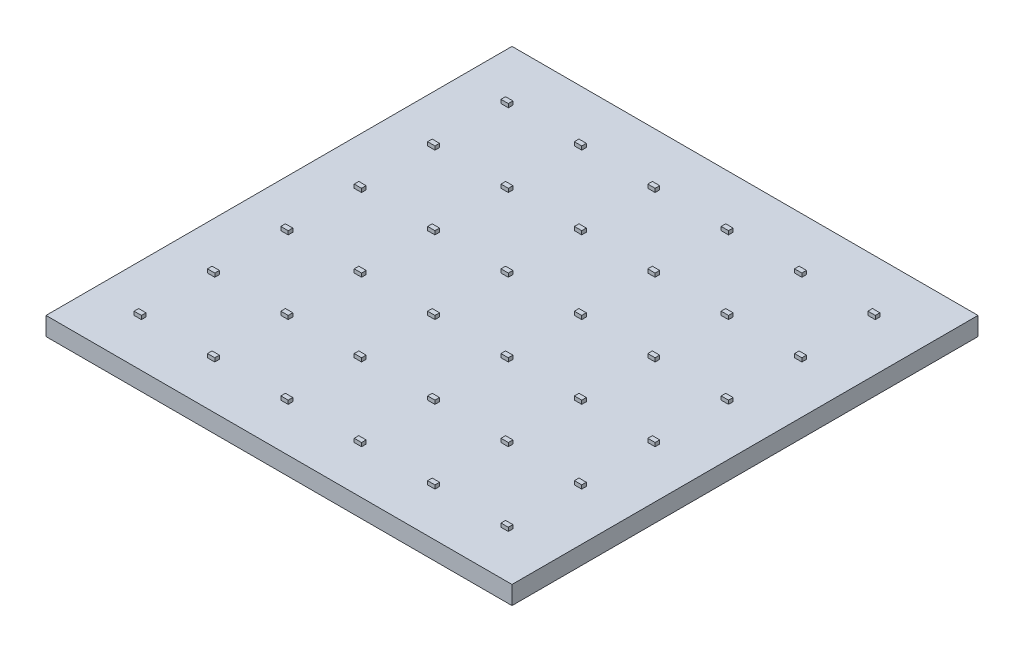
SolidWorks part; units mm, degrees
ref_plane "Front Plane" through (0, 0, 0) normal (0, 0, 1) x (1, 0, 0)
ref_plane "Top Plane" through (0, 0, 0) normal (0, 1, 0) x (1, 0, 0)
ref_plane "Right Plane" through (0, 0, 0) normal (1, 0, 0) x (0, 0, -1)
sketch "Sketch4" plane through (0, 0, 0) normal (0, 1, 0) x (1, 0, 0)
  line L1 (-74.2664, 89.4273) -> (52.7336, 89.4273)
  line L2 (-74.2664, 89.4273) -> (-74.2664, -37.5727)
  line L3 (-74.2664, -37.5727) -> (52.7336, -37.5727)
  line L4 (52.7336, 89.4273) -> (52.7336, -37.5727)
  dimension "D1" = 127
  dimension "D2" = 127
extrude "Boss-Extrude5" add sketch "Sketch4" along normal blind 5
sketch "Sketch5" plane through (0, 5, 0) normal (0, 1, 0) x (1, 0, 0)
  line L0 (-42.2664, -25.5727) -> (-42.2664, -24.3227)
  line L1 (-62.2664, -25.5727) -> (-60.2664, -25.5727)
  line L2 (-62.2664, -25.5727) -> (-62.2664, -24.3227)
  line L3 (-62.2664, -24.3227) -> (-60.2664, -24.3227)
  line L4 (-60.2664, -25.5727) -> (-60.2664, -24.3227)
  line L5 (-42.2664, -25.5727) -> (-40.2664, -25.5727)
  line L6 (-40.2664, -25.5727) -> (-40.2664, -24.3227)
  line L7 (-42.2664, -24.3227) -> (-40.2664, -24.3227)
  line L8 (-22.2664, -25.5727) -> (-22.2664, -24.3227)
  line L9 (-22.2664, -25.5727) -> (-20.2664, -25.5727)
  line L10 (-20.2664, -25.5727) -> (-20.2664, -24.3227)
  line L11 (-22.2664, -24.3227) -> (-20.2664, -24.3227)
  line L12 (-2.2664, -25.5727) -> (-2.2664, -24.3227)
  line L13 (-2.2664, -25.5727) -> (-0.2664, -25.5727)
  line L14 (-0.2664, -25.5727) -> (-0.2664, -24.3227)
  line L15 (-2.2664, -24.3227) -> (-0.2664, -24.3227)
  line L16 (17.7336, -25.5727) -> (17.7336, -24.3227)
  line L17 (17.7336, -25.5727) -> (19.7336, -25.5727)
  line L18 (19.7336, -25.5727) -> (19.7336, -24.3227)
  line L19 (17.7336, -24.3227) -> (19.7336, -24.3227)
  line L20 (37.7336, -25.5727) -> (37.7336, -24.3227)
  line L21 (37.7336, -25.5727) -> (39.7336, -25.5727)
  line L22 (39.7336, -25.5727) -> (39.7336, -24.3227)
  line L23 (37.7336, -24.3227) -> (39.7336, -24.3227)
  line L24 (-42.2664, -5.5727) -> (-42.2664, -4.3227)
  line L25 (-42.2664, -5.5727) -> (-40.2664, -5.5727)
  line L26 (-40.2664, -5.5727) -> (-40.2664, -4.3227)
  line L27 (-42.2664, -4.3227) -> (-40.2664, -4.3227)
  line L28 (-22.2664, -5.5727) -> (-22.2664, -4.3227)
  line L29 (-22.2664, -5.5727) -> (-20.2664, -5.5727)
  line L30 (-20.2664, -5.5727) -> (-20.2664, -4.3227)
  line L31 (-22.2664, -4.3227) -> (-20.2664, -4.3227)
  line L32 (-2.2664, -5.5727) -> (-2.2664, -4.3227)
  line L33 (-2.2664, -5.5727) -> (-0.2664, -5.5727)
  line L34 (-0.2664, -5.5727) -> (-0.2664, -4.3227)
  line L35 (-2.2664, -4.3227) -> (-0.2664, -4.3227)
  line L36 (17.7336, -5.5727) -> (17.7336, -4.3227)
  line L37 (17.7336, -5.5727) -> (19.7336, -5.5727)
  line L38 (19.7336, -5.5727) -> (19.7336, -4.3227)
  line L39 (17.7336, -4.3227) -> (19.7336, -4.3227)
  line L40 (37.7336, -5.5727) -> (37.7336, -4.3227)
  line L41 (37.7336, -5.5727) -> (39.7336, -5.5727)
  line L42 (39.7336, -5.5727) -> (39.7336, -4.3227)
  line L43 (37.7336, -4.3227) -> (39.7336, -4.3227)
  line L44 (-42.2664, 14.4273) -> (-42.2664, 15.6773)
  line L45 (-42.2664, 14.4273) -> (-40.2664, 14.4273)
  line L46 (-40.2664, 14.4273) -> (-40.2664, 15.6773)
  line L47 (-42.2664, 15.6773) -> (-40.2664, 15.6773)
  line L48 (-22.2664, 14.4273) -> (-22.2664, 15.6773)
  line L49 (-22.2664, 14.4273) -> (-20.2664, 14.4273)
  line L50 (-20.2664, 14.4273) -> (-20.2664, 15.6773)
  line L51 (-22.2664, 15.6773) -> (-20.2664, 15.6773)
  line L52 (-2.2664, 14.4273) -> (-2.2664, 15.6773)
  line L53 (-2.2664, 14.4273) -> (-0.2664, 14.4273)
  line L54 (-0.2664, 14.4273) -> (-0.2664, 15.6773)
  line L55 (-2.2664, 15.6773) -> (-0.2664, 15.6773)
  line L56 (17.7336, 14.4273) -> (17.7336, 15.6773)
  line L57 (17.7336, 14.4273) -> (19.7336, 14.4273)
  line L58 (19.7336, 14.4273) -> (19.7336, 15.6773)
  line L59 (17.7336, 15.6773) -> (19.7336, 15.6773)
  line L60 (37.7336, 14.4273) -> (37.7336, 15.6773)
  line L61 (37.7336, 14.4273) -> (39.7336, 14.4273)
  line L62 (39.7336, 14.4273) -> (39.7336, 15.6773)
  line L63 (37.7336, 15.6773) -> (39.7336, 15.6773)
  line L64 (-42.2664, 34.4273) -> (-42.2664, 35.6773)
  line L65 (-42.2664, 34.4273) -> (-40.2664, 34.4273)
  line L66 (-40.2664, 34.4273) -> (-40.2664, 35.6773)
  line L67 (-42.2664, 35.6773) -> (-40.2664, 35.6773)
  line L68 (-22.2664, 34.4273) -> (-22.2664, 35.6773)
  line L69 (-22.2664, 34.4273) -> (-20.2664, 34.4273)
  line L70 (-20.2664, 34.4273) -> (-20.2664, 35.6773)
  line L71 (-22.2664, 35.6773) -> (-20.2664, 35.6773)
  line L72 (-2.2664, 34.4273) -> (-2.2664, 35.6773)
  line L73 (-2.2664, 34.4273) -> (-0.2664, 34.4273)
  line L74 (-0.2664, 34.4273) -> (-0.2664, 35.6773)
  line L75 (-2.2664, 35.6773) -> (-0.2664, 35.6773)
  line L76 (17.7336, 34.4273) -> (17.7336, 35.6773)
  line L77 (17.7336, 34.4273) -> (19.7336, 34.4273)
  line L78 (19.7336, 34.4273) -> (19.7336, 35.6773)
  line L79 (17.7336, 35.6773) -> (19.7336, 35.6773)
  line L80 (37.7336, 34.4273) -> (37.7336, 35.6773)
  line L81 (37.7336, 34.4273) -> (39.7336, 34.4273)
  line L82 (39.7336, 34.4273) -> (39.7336, 35.6773)
  line L83 (37.7336, 35.6773) -> (39.7336, 35.6773)
  line L84 (-42.2664, 54.4273) -> (-42.2664, 55.6773)
  line L85 (-42.2664, 54.4273) -> (-40.2664, 54.4273)
  line L86 (-40.2664, 54.4273) -> (-40.2664, 55.6773)
  line L87 (-42.2664, 55.6773) -> (-40.2664, 55.6773)
  line L88 (-22.2664, 54.4273) -> (-22.2664, 55.6773)
  line L89 (-22.2664, 54.4273) -> (-20.2664, 54.4273)
  line L90 (-20.2664, 54.4273) -> (-20.2664, 55.6773)
  line L91 (-22.2664, 55.6773) -> (-20.2664, 55.6773)
  line L92 (-2.2664, 54.4273) -> (-2.2664, 55.6773)
  line L93 (-2.2664, 54.4273) -> (-0.2664, 54.4273)
  line L94 (-0.2664, 54.4273) -> (-0.2664, 55.6773)
  line L95 (-2.2664, 55.6773) -> (-0.2664, 55.6773)
  line L96 (17.7336, 54.4273) -> (17.7336, 55.6773)
  line L97 (17.7336, 54.4273) -> (19.7336, 54.4273)
  line L98 (19.7336, 54.4273) -> (19.7336, 55.6773)
  line L99 (17.7336, 55.6773) -> (19.7336, 55.6773)
  line L100 (37.7336, 54.4273) -> (37.7336, 55.6773)
  line L101 (37.7336, 54.4273) -> (39.7336, 54.4273)
  line L102 (39.7336, 54.4273) -> (39.7336, 55.6773)
  line L103 (37.7336, 55.6773) -> (39.7336, 55.6773)
  line L104 (-42.2664, 74.4273) -> (-42.2664, 75.6773)
  line L105 (-42.2664, 74.4273) -> (-40.2664, 74.4273)
  line L106 (-40.2664, 74.4273) -> (-40.2664, 75.6773)
  line L107 (-42.2664, 75.6773) -> (-40.2664, 75.6773)
  line L108 (-22.2664, 74.4273) -> (-22.2664, 75.6773)
  line L109 (-22.2664, 74.4273) -> (-20.2664, 74.4273)
  line L110 (-20.2664, 74.4273) -> (-20.2664, 75.6773)
  line L111 (-22.2664, 75.6773) -> (-20.2664, 75.6773)
  line L112 (-2.2664, 74.4273) -> (-2.2664, 75.6773)
  line L113 (-2.2664, 74.4273) -> (-0.2664, 74.4273)
  line L114 (-0.2664, 74.4273) -> (-0.2664, 75.6773)
  line L115 (-2.2664, 75.6773) -> (-0.2664, 75.6773)
  line L116 (17.7336, 74.4273) -> (17.7336, 75.6773)
  line L117 (17.7336, 74.4273) -> (19.7336, 74.4273)
  line L118 (19.7336, 74.4273) -> (19.7336, 75.6773)
  line L119 (17.7336, 75.6773) -> (19.7336, 75.6773)
  line L120 (37.7336, 74.4273) -> (37.7336, 75.6773)
  line L121 (37.7336, 74.4273) -> (39.7336, 74.4273)
  line L122 (39.7336, 74.4273) -> (39.7336, 75.6773)
  line L123 (37.7336, 75.6773) -> (39.7336, 75.6773)
  line L124 (-62.2664, -5.5727) -> (-62.2664, -4.3227)
  line L125 (-62.2664, -5.5727) -> (-60.2664, -5.5727)
  line L126 (-60.2664, -5.5727) -> (-60.2664, -4.3227)
  line L127 (-62.2664, -4.3227) -> (-60.2664, -4.3227)
  line L128 (-62.2664, 14.4273) -> (-62.2664, 15.6773)
  line L129 (-62.2664, 14.4273) -> (-60.2664, 14.4273)
  line L130 (-60.2664, 14.4273) -> (-60.2664, 15.6773)
  line L131 (-62.2664, 15.6773) -> (-60.2664, 15.6773)
  line L132 (-62.2664, 34.4273) -> (-62.2664, 35.6773)
  line L133 (-62.2664, 34.4273) -> (-60.2664, 34.4273)
  line L134 (-60.2664, 34.4273) -> (-60.2664, 35.6773)
  line L135 (-62.2664, 35.6773) -> (-60.2664, 35.6773)
  line L136 (-62.2664, 54.4273) -> (-62.2664, 55.6773)
  line L137 (-62.2664, 54.4273) -> (-60.2664, 54.4273)
  line L138 (-60.2664, 54.4273) -> (-60.2664, 55.6773)
  line L139 (-62.2664, 55.6773) -> (-60.2664, 55.6773)
  line L140 (-62.2664, 74.4273) -> (-62.2664, 75.6773)
  line L141 (-62.2664, 74.4273) -> (-60.2664, 74.4273)
  line L142 (-60.2664, 74.4273) -> (-60.2664, 75.6773)
  line L143 (-62.2664, 75.6773) -> (-60.2664, 75.6773)
  line L144 (-74.2664, -37.5727) -> (52.7336, -37.5727) construction
  line L145 (-74.2664, 89.4273) -> (-74.2664, -37.5727) construction
  dimension "D1" = 1.25
  dimension "D2" = 2
  dimension "D5" = 12
  dimension "D6" = 12
  dimension "D3" = 6
  dimension "D4" = 6
extrude "Boss-Extrude6" add sketch "Sketch5" along normal blind 1
